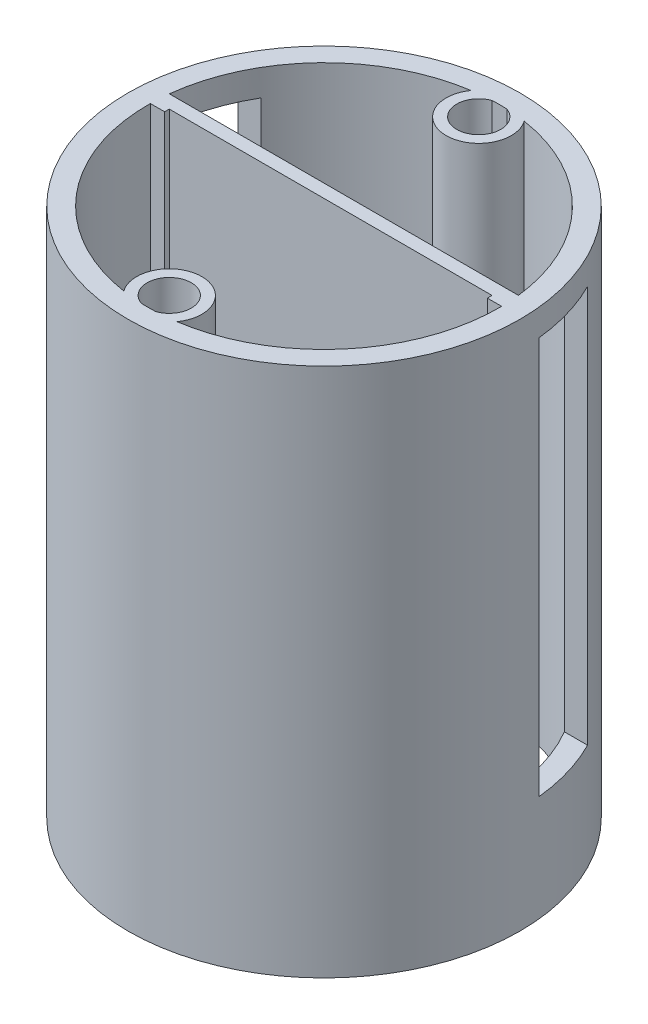
SolidWorks part; units mm, degrees
ref_plane "Front Plane" through (0, 0, 0) normal (0, 0, 1) x (1, 0, 0)
ref_plane "Top Plane" through (0, 0, 0) normal (0, 1, 0) x (1, 0, 0)
ref_plane "Right Plane" through (0, 0, 0) normal (1, 0, 0) x (0, 0, -1)
sketch "Sketch1" plane through (0, 0, 0) normal (0, 1, 0) x (1, 0, 0)
  line L0 (-35.144, 1.2725) -> (-35.144, -0.5055)
  line L5 (-35.144, 1.2725) -> (-30.9263, 1.2725)
  line L7 (35.144, 1.2725) -> (35.144, -0.5055)
  line L8 (-30.9263, 1.2725) -> (-30.9263, 3.8125)
  line L9 (-30.9263, 3.8125) -> (-33.4663, 3.8125)
  line L10 (-35.144, -0.5055) -> (-31.0048, -0.5055)
  line L11 (-31.0048, -0.5055) -> (-31.0048, -3.0455)
  line L12 (-31.0048, -3.0455) -> (-33.5448, -3.0455)
  line L13 (0, -2.2231) -> (0, 2.2231) construction
  line L14 (31.0048, -3.0455) -> (33.5448, -3.0455)
  line L15 (31.0048, -0.5055) -> (31.0048, -3.0455)
  line L16 (35.144, -0.5055) -> (31.0048, -0.5055)
  line L17 (35.144, 1.2725) -> (30.9263, 1.2725)
  line L18 (30.9263, 1.2725) -> (30.9263, 3.8125)
  line L19 (30.9263, 3.8125) -> (33.4663, 3.8125)
  circle A0 centre (0, 0) radius 37.592
  arc A3 (-33.5448, -3.0455) -> (33.5448, -3.0455) centre (0, 0) ccw construction
  arc A4 (-33.5448, -3.0455) -> (33.5448, -3.0455) centre (0, 0) ccw
  arc A5 (33.4663, 3.8125) -> (-33.4663, 3.8125) centre (0, 0) ccw construction
  arc A6 (33.4663, 3.8125) -> (-33.4663, 3.8125) centre (0, 0) ccw
  point P4 (-35.144, 0.3835)
  point P18 (0, 0)
  dimension "D1" = 75.184
  dimension "D2" = 2.54
  dimension "D3" = 35.144
  dimension "D4" = 35.144
  dimension "D6" = 2.54
  dimension "D7" = 2.54
  dimension "D8" = 1.778
extrude "Boss-Extrude1" add sketch "Sketch1" along normal blind 50.8
sketch "Sketch4" plane through (0, 50.8, 0) normal (0, 1, 0) x (1, 0, 0)
  line L1 (33.4663, 3.8125) -> (-33.4663, 3.8125)
  line L2 (-30.9263, 1.2725) -> (30.9263, 1.2725)
  line L3 (30.9263, 1.2725) -> (31.0048, -0.5055) construction
  line L4 (-30.9263, 1.2725) -> (-31.0048, -0.5055) construction
  line L5 (-30.9263, 1.2725) -> (-30.9656, 0.3835)
  line L6 (-30.9656, 0.3835) -> (-33.6806, 0.3835)
  line L7 (30.9263, 1.2725) -> (30.9656, 0.3835)
  line L8 (30.9656, 0.3835) -> (33.6806, 0.3835)
  circle A2 centre (0, 0) radius 37.592
  arc A5 (33.4663, 3.8125) -> (-33.4663, 3.8125) centre (0, 0) ccw
  arc A6 (-33.6806, 0.3835) -> (33.6806, 0.3835) centre (0, 0) ccw
  dimension "D1" = 75.184
extrude "Boss-Extrude2" add sketch "Sketch4" along normal blind 50.8
sketch "Sketch5" plane through (0, 0, 0) normal (0, -1, 0) x (1, 0, 0)
  line L0 (-3.4506, 0) -> (3.4506, 0) construction
  circle A0 centre (0, -29.6706) radius 4.2227
  circle A1 centre (0, -29.6706) radius 6.2547
  circle A2 centre (0, 29.6706) radius 4.2227
  circle A3 centre (0, 29.6706) radius 6.2548
  point P6 (0, 0)
  dimension "D1" = 8.4455
  dimension "D2" = 2.032
extrude "Boss-Extrude3" add sketch "Sketch5" against normal blind 101.6
sketch "Sketch6" plane through (0, 0, 0) normal (1, 0, 0) x (0, 0, -1)
  line L8 (3.8125, 101.6) -> (3.8125, 0) construction
  line L9 (3.8125, 96.52) -> (17.0205, 96.52)
  line L10 (3.8125, 96.52) -> (3.8125, 20.32)
  line L11 (3.8125, 20.32) -> (17.0205, 20.32)
  line L12 (17.0205, 96.52) -> (17.0205, 20.32)
  dimension "D1" = 13.208
  dimension "D2" = 76.2
extrude "Cut-Extrude1" cut sketch "Sketch6" against normal blind 64.516 and the other way blind 60.198
